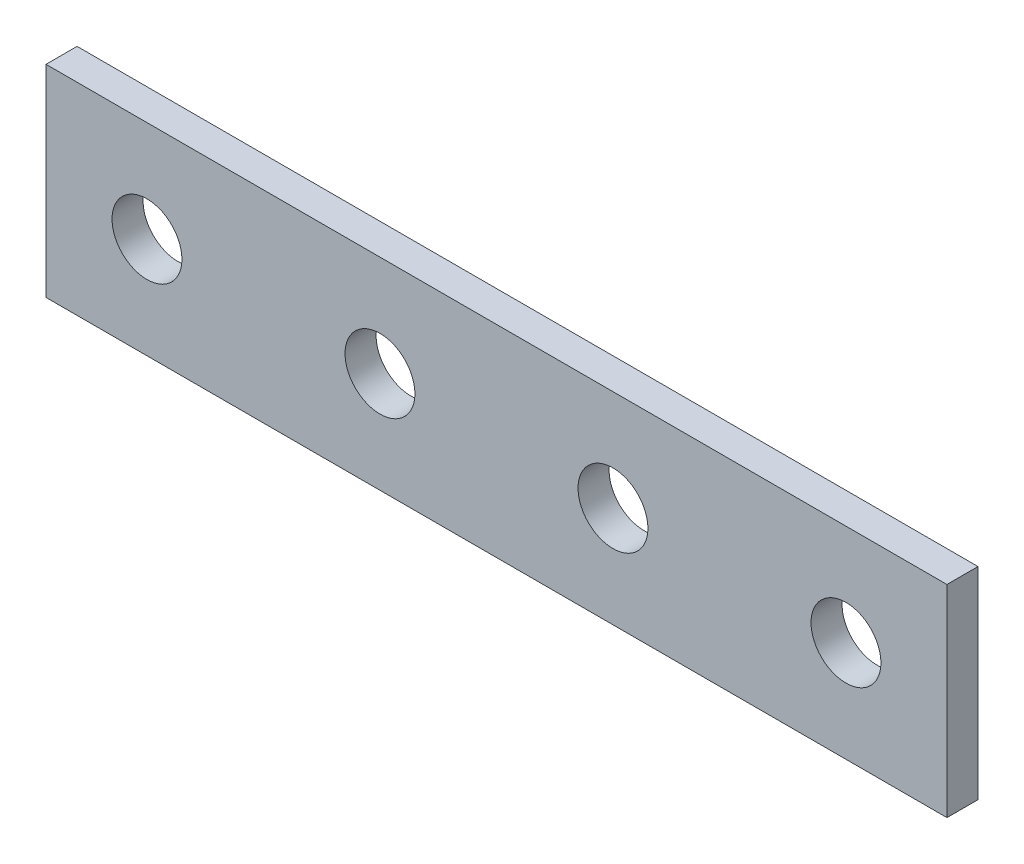
SolidWorks part; units mm, degrees
ref_plane "Front Plane" through (0, 0, 0) normal (0, 0, 1) x (1, 0, 0)
ref_plane "Top Plane" through (0, 0, 0) normal (0, 1, 0) x (1, 0, 0)
ref_plane "Right Plane" through (0, 0, 0) normal (1, 0, 0) x (0, 0, -1)
sketch "Sketch1" plane through (0, 0, 0) normal (0, 0, 1) x (1, 0, 0)
  line L0 (-92.075, 0) -> (92.075, 0) construction
  line L1 (-92.075, 20.6375) -> (92.075, 20.6375)
  line L2 (-92.075, 20.6375) -> (-92.075, -20.6375)
  line L3 (-92.075, -20.6375) -> (92.075, -20.6375)
  line L4 (92.075, 20.6375) -> (92.075, -20.6375)
  circle A0 centre (-71.4375, 0) radius 7.1438
  circle A1 centre (-23.8125, 0) radius 7.1438
  circle A2 centre (23.8125, 0) radius 7.1438
  circle A3 centre (71.4375, 0) radius 7.1437
  dimension "Hole Size" = 14.2875
  dimension "B" = 184.15
  dimension "Spacing" = 47.625
  dimension "D4" = 47.625
  dimension "D5" = 47.625
  dimension "end location" = 23.8125
  dimension "A" = 41.275
extrude "Boss-Extrude1" add sketch "Sketch1" along normal mid plane 6.35
sketch "Sketch2" plane through (0, 0, 3.175) normal (0, 0, 1) x (1, 0, 0)
  line L4 (-92.075, 20.6375) -> (-92.075, -20.6375)
  line L5 (-92.075, -20.6375) -> (92.075, -20.6375)
  line L6 (92.075, -20.6375) -> (92.075, 20.6375)
  line L7 (92.075, 20.6375) -> (-92.075, 20.6375)
  line L8 (-92.075, 20.6375) -> (-92.075, -20.6375)
  line L9 (-92.075, -20.6375) -> (92.075, -20.6375)
  line L10 (92.075, -20.6375) -> (92.075, 20.6375)
  line L11 (92.075, 20.6375) -> (-92.075, 20.6375)
  dimension "D1" = 0
extrude "Boss-Extrude2" [suppressed] add sketch "Sketch2" against normal up to surface (6.35 mm away)
equation "\"end location@Sketch1\" = \"Spacing@Sketch1\"/2"
equation "\"D5@Sketch1\" = \"Spacing@Sketch1\""
equation "\"D4@Sketch1\" = \"Spacing@Sketch1\""
